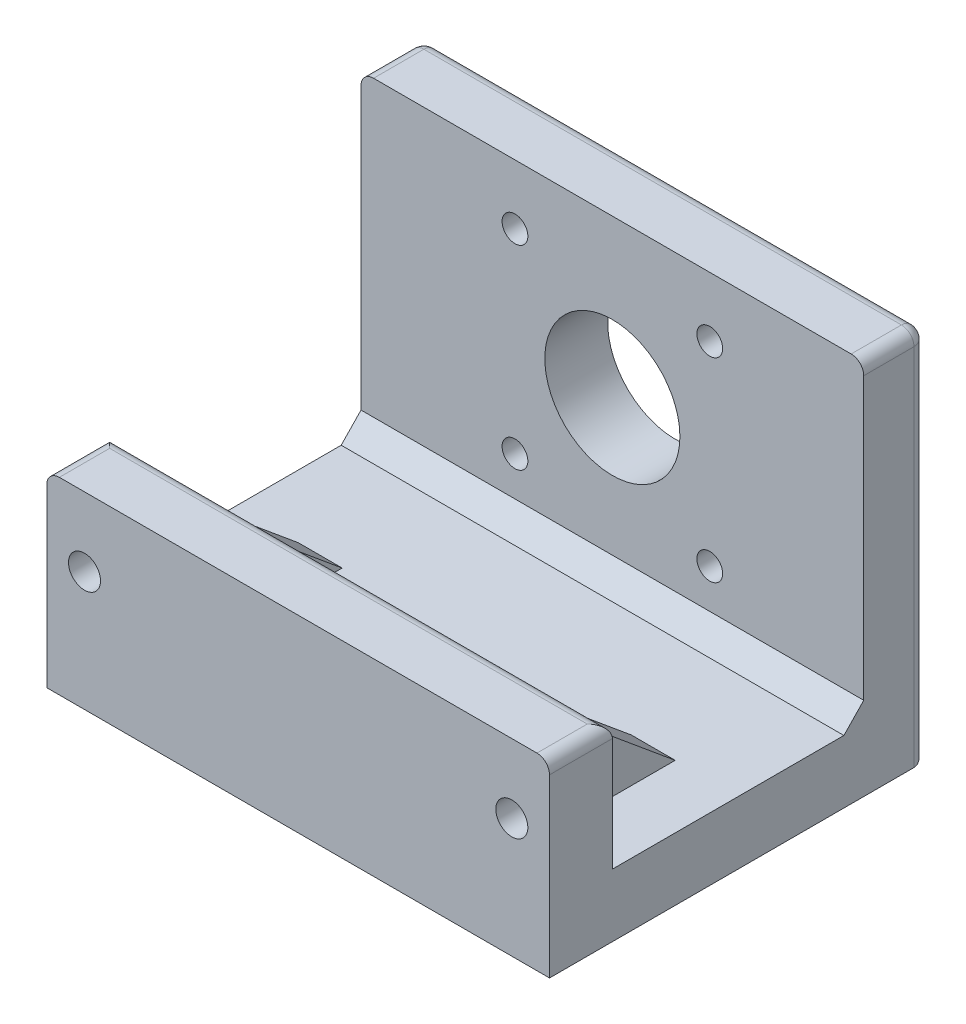
SolidWorks part; units mm, degrees
ref_plane "Front Plane" through (0, 0, 0) normal (0, 0, 1) x (1, 0, 0)
ref_plane "Top Plane" through (0, 0, 0) normal (0, 1, 0) x (1, 0, 0)
ref_plane "Right Plane" through (0, 0, 0) normal (1, 0, 0) x (0, 0, -1)
sketch "Sketch1" plane through (0, 0, 0) normal (0, 1, 0) x (1, 0, 0)
  line L1 (-40, -30) -> (40, -30)
  line L2 (-40, -30) -> (-40, 30)
  line L3 (-40, 30) -> (40, 30)
  line L4 (40, -30) -> (40, 30)
  line L5 (-40, -30) -> (40, 30) construction
  line L6 (-40, 30) -> (40, -30) construction
  point P0 (0, 0)
  dimension "D1" = 80
  dimension "D2" = 60
extrude "Boss-Extrude1" add sketch "Sketch1" along normal blind 60
sketch "Sketch2" plane through (0, 60, 0) normal (0, 1, 0) x (1, 0, 0)
  line L1 (47.9449, -20) -> (-47.9449, -20)
  line L2 (47.9449, -20) -> (47.9449, 20)
  line L3 (47.9449, 20) -> (-47.9449, 20)
  line L4 (-47.9449, -20) -> (-47.9449, 20)
  line L5 (47.9449, -20) -> (-47.9449, 20) construction
  line L6 (47.9449, 20) -> (-47.9449, -20) construction
  point P0 (0, 0)
  dimension "D1" = 40
extrude "Cut-Extrude1" cut sketch "Sketch2" against normal blind 50
sketch "Sketch3" plane through (0, 60, 0) normal (0, 1, 0) x (1, 0, 0)
  line L1 (-40, -20) -> (40, -20)
  line L2 (-40, -20) -> (-40, -30)
  line L3 (-40, -30) -> (40, -30)
  line L4 (40, -20) -> (40, -30)
extrude "Cut-Extrude2" cut sketch "Sketch3" against normal blind 30
sketch "Sketch5" plane through (0, 0, 0) normal (0, -1, 0) x (1, 0, 0)
  line L0 (-40, -30) -> (-40, 30) construction
  line L1 (40, -30) -> (-40, -30) construction
  line L2 (0, 0) -> (0, -37.2135) construction
  circle A0 centre (-30, 0.5) radius 4.1
  circle A1 centre (30, 0.5) radius 4.1
  dimension "D1" = 8.2
  dimension "D2" = 10
  dimension "D3" = 30.5
extrude "Cut-Extrude3" cut sketch "Sketch5" against normal blind 7
sketch "Sketch6" plane through (0, 0, 20) normal (0, 0, -1) x (-1, 0, 0)
  line L0 (40, 10) -> (-40, 10) construction
  line L1 (-30, 10) -> (-23, 10)
  line L2 (-30, 10) -> (-30, 26.5998)
  line L3 (-30, 26.5998) -> (-23, 26.5998)
  line L4 (-23, 10) -> (-23, 26.5998)
  line L5 (-40, 10) -> (-40, 30) construction
  line L6 (0, 57.3535) -> (0, 2.6465) construction
  line L8 (30, 26.5998) -> (23, 26.5998)
  line L9 (23, 10) -> (23, 26.5998)
  line L10 (30, 10) -> (23, 10)
  line L11 (30, 10) -> (30, 26.5998)
  point P11 (0, 30)
  dimension "D1" = 7
  dimension "D2" = 10
  dimension "D3" = 7
sketch "Sketch8" plane through (0, 0, -20) normal (0, 0, 1) x (1, 0, 0)
  line L0 (0, 124.8047) -> (0, -4.8047) construction
  line L2 (-140.4211, 35) -> (60.4211, 35) construction
  circle A0 centre (0, 35) radius 10.75
  point P3 (0, 60)
  point P7 (-40, 35)
  dimension "D1" = 21.5
extrude "Cut-Extrude5" cut sketch "Sketch8" against normal through all
sketch "Sketch12" plane through (0, 0, -20) normal (0, 0, 1) x (1, 0, 0)
  line L5 (-15.5, 19.5) -> (15.5, 50.5) construction
  line L6 (-15.5, 50.5) -> (15.5, 19.5) construction
  circle A0 centre (-15.5, 50.5) radius 2.05
  circle A1 centre (15.5, 50.5) radius 2.05
  circle A2 centre (15.5, 19.5) radius 2.05
  circle A3 centre (-15.5, 19.5) radius 2.05
  point P0 (0, 35)
  point P1 (0, 35)
  point P17 (0, 35)
  dimension "D3" = 4.1
  dimension "D1" = 31
  dimension "D2" = 31
  dimension "D4" = 4
extrude "Cut-Extrude8" cut sketch "Sketch12" against normal through all contours A1 | A3 | A0 | A2
fillet "Fillet1" radius 2 9 edges at (-40, 30, 25) (40, 30, 25) (0, 30, 20) (40, 30, -30) (0, 0, -30) (40, 60, -25) (-40, 60, -25) (-40, 30, -30) (0, 60, -30)
sketch "Sketch13" plane through (0, 0, 20) normal (0, 0, -1) x (-1, 0, 0)
  line L0 (-40, 10) -> (-40, 28) construction
  line L1 (40, 28) -> (-40, 28) construction
  line L2 (40, 28) -> (40, 10) construction
  circle A0 centre (-34, 19) radius 2.55
  circle A1 centre (34, 19) radius 2.55
  dimension "D1" = 5.1
  dimension "D2" = 6
  dimension "D3" = 9
  dimension "D4" = 5.1
  dimension "D5" = 9
  dimension "D6" = 6
extrude "Cut-Extrude9" cut sketch "Sketch13" against normal through all
extrude "Boss-Extrude2" add sketch "Sketch6" along normal blind 20
sketch "Sketch14" plane through (-30, 0, 0) normal (-1, 0, 0) x (0, 0, 1)
  line L0 (0, 10) -> (20, 26.5998)
  line L1 (0, 10) -> (0, 26.5998)
  line L2 (0, 26.5998) -> (20, 26.5998)
extrude "Cut-Extrude10" cut sketch "Sketch14" against normal through all both and the other way through all contours L2 L0 L1
sketch "Sketch15" plane through (0, 0, 0) normal (1, 0, 0) x (0, 0, -1)
  line L0 (20, 13.27) -> (16.8468, 10)
  line L1 (20, 58) -> (20, 10) construction
  line L2 (-20, 10) -> (20, 10) construction
  line L3 (16.8468, 10) -> (20, 10)
  line L4 (20, 10) -> (20, 13.27)
  dimension "3.27" = 3.27
extrude "Boss-Extrude3" add sketch "Sketch15" along normal mid plane 80
